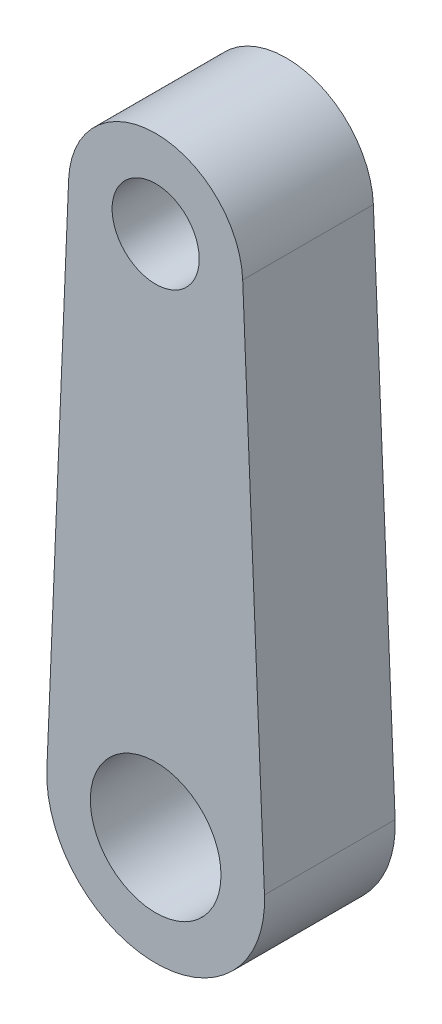
SolidWorks part; units mm, degrees
ref_plane "Front Plane" through (0, 0, 0) normal (0, 0, 1) x (1, 0, 0)
ref_plane "Top Plane" through (0, 0, 0) normal (0, 1, 0) x (1, 0, 0)
ref_plane "Right Plane" through (0, 0, 0) normal (1, 0, 0) x (0, 0, -1)
sketch "Sketch1" plane through (0, 0, 0) normal (0, 0, 1) x (1, 0, 0)
  line L0 (0, -6) -> (0, 6) construction
  line L1 (1.9983, 6.0833) -> (2.4978, -5.8958)
  line L2 (-2.4978, -5.8958) -> (-1.9983, 6.0833)
  circle A0 centre (0, 6) radius 1
  circle A1 centre (0, -6) radius 1.5
  arc A2 (1.9983, 6.0833) -> (-1.9983, 6.0833) centre (0, 6) ccw
  arc A3 (-2.4978, -5.8958) -> (2.4978, -5.8958) centre (0, -6) ccw
  circle A4 centre (0, 6) radius 2 construction
  circle A5 centre (0, -6) radius 2.5 construction
  point P4 (0, 0)
  dimension "D2" = 3
  dimension "D3" = 2
  dimension "D1" = 12
  dimension "D4" = 1
extrude "Boss-Extrude1" add sketch "Sketch1" along normal blind 3
